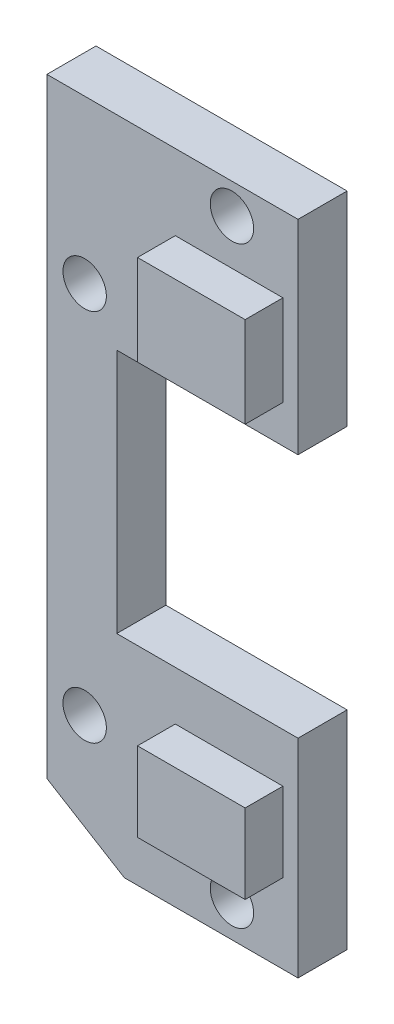
SolidWorks part; units mm, degrees
ref_plane "前视基准面" through (0, 0, 0) normal (0, 0, 1) x (1, 0, 0)
ref_plane "上视基准面" through (0, 0, 0) normal (0, 1, 0) x (1, 0, 0)
ref_plane "右视基准面" through (0, 0, 0) normal (1, 0, 0) x (0, 0, -1)
other "Configuration Table"
sketch "USB end crossbar with open connector relief profile" plane through (0, 0, 0) normal (0, 0, 1) x (1, 0, 0)
  line L0 (-38.8, -21.5) -> (-34.7, -24)
  line L1 (-34.7, -24) -> (-25.5, -24)
  line L2 (-25.5, -24) -> (-25.5, -13)
  line L3 (-25.5, -13) -> (-35.1, -13)
  line L4 (-35.1, -13) -> (-35.1, 0)
  line L5 (-35.1, 0) -> (-25.5, 0)
  line L6 (-25.5, 0) -> (-25.5, 10.8)
  line L7 (-25.5, 10.8) -> (-38.8, 10.8)
  line L8 (-38.8, 10.8) -> (-38.8, -21.5)
  circle A0 centre (-36.8, -17.6) radius 1.15
  circle A1 centre (-36.8, 2.2) radius 1.15
  circle A2 centre (-29, -22.2) radius 1.15
  circle A3 centre (-29, 9.2) radius 1.15
extrude "USB end crossbar with open connector relief" add sketch "USB end crossbar with open connector relief profile" along normal blind 2.6
sketch "Two PCB rests beside Type-C, no support under connector profile" plane through (0, 0, 0) normal (0, 0, 1) x (1, 0, 0)
  line L0 (-32, -19.8) -> (-26.3, -19.8)
  line L1 (-26.3, -19.8) -> (-26.3, -15.6)
  line L2 (-26.3, -15.6) -> (-32, -15.6)
  line L3 (-32, -15.6) -> (-32, -19.8)
  line L4 (-32, 2) -> (-26.3, 2)
  line L5 (-26.3, 2) -> (-26.3, 6.8)
  line L6 (-26.3, 6.8) -> (-32, 6.8)
  line L7 (-32, 6.8) -> (-32, 2)
extrude "Two PCB rests beside Type-C, no support under connector" add sketch "Two PCB rests beside Type-C, no support under connector profile" along normal blind 2 from offset 2.6
